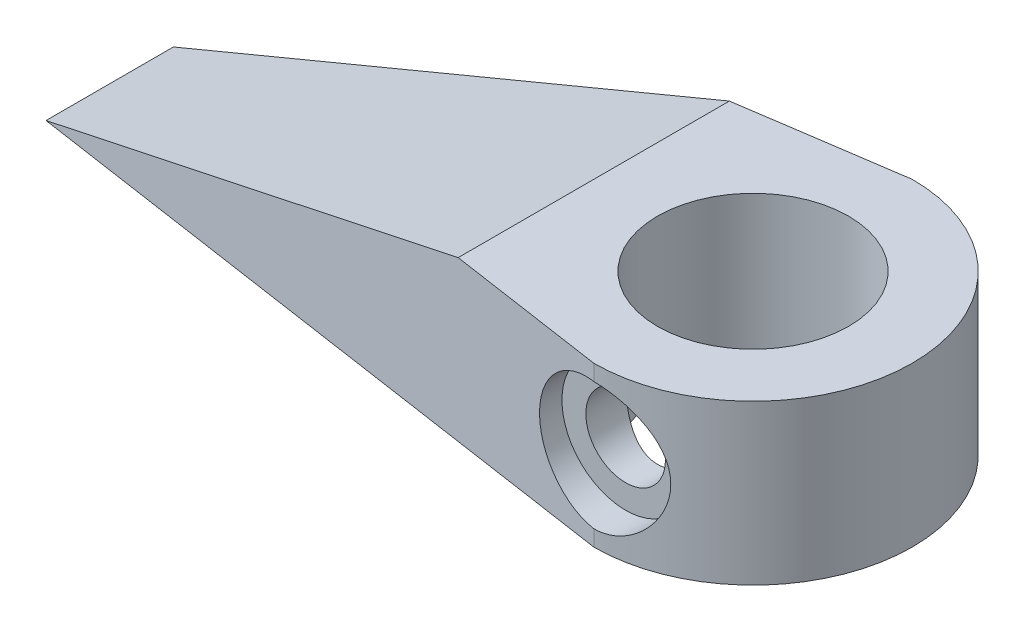
SolidWorks part; units mm, degrees
ref_plane "Front Plane" through (0, 0, 0) normal (0, 0, 1) x (1, 0, 0)
ref_plane "Top Plane" through (0, 0, 0) normal (0, 1, 0) x (1, 0, 0)
ref_plane "Right Plane" through (0, 0, 0) normal (1, 0, 0) x (0, 0, -1)
sketch "Sketch1" plane through (0, 0, 0) normal (0, 0, 1) x (1, 0, 0)
  line L0 (0, 0) -> (15.1987, 5)
  line L1 (15.1987, 5) -> (15.1987, 0)
  line L2 (15.1987, 0) -> (0, 0)
  dimension "D1" = 5
  dimension "D2" = 16
extrude "Boss-Extrude4" add sketch "Sketch1" along normal blind 4
sketch "Sketch7" plane through (0, 0, 0) normal (0, 1, 0) x (1, 0, 0)
  line L0 (15.1987, -2) -> (25.1987, -2) construction
  line L1 (15.1987, -4) -> (15.1987, 0) construction
  line L10 (20.1987, 3) -> (0, 0)
  line L11 (0, 0) -> (15.1987, 0)
  line L12 (15.1987, 0) -> (15.1987, -4)
  line L13 (15.1987, -4) -> (0, -4)
  line L14 (0, -4) -> (20.1987, -7)
  arc A0 (20.1987, -7) -> (20.1987, 3) centre (20.1987, -2) ccw
  dimension "D1" = 10
  dimension "D2" = 5
extrude "Boss-Extrude6" add sketch "Sketch7" along normal blind 5
sketch "Sketch10" plane through (0, 0, 0) normal (0, 0, 1) x (1, 0, 0)
  line L3 (0, 0) -> (0, 5)
  line L4 (0, 5) -> (15.1987, 5)
  line L5 (15.1987, 5) -> (0, 0)
extrude "Cut-Extrude3" cut sketch "Sketch10" against normal up to next
ref_plane "Plane1" through (0, 0, 2) normal (0, 0, 1) x (1, 0, 0)
sketch "Sketch9" plane through (0, 5, 0) normal (0, 1, 0) x (1, 0, 0)
  line L0 (-2.75, -2) -> (2.75, -2) construction
  circle A0 centre (20.1987, -2) radius 3
  arc A1 (20.1987, -7) -> (20.1987, 3) centre (20.1987, -2) ccw construction
  dimension "D1" = 6
extrude "Cut-Extrude2" cut sketch "Sketch9" against normal up to next
mirror "Mirror1" about plane through (0, 0, 2) normal (0, 0, 1) of "Cut-Extrude3"
ref_plane "Plane2" through (20.1987, 5, 7) normal (0, -1, 0) x (-1, 0, 0)
ref_plane "Plane3" through (0, 0, 7) normal (0, 0, 1) x (1, 0, 0)
sketch "Sketch12" plane through (0, 0, 7) normal (0, 0, 1) x (1, 0, 0)
  line L0 (20.1987, 5) -> (20.1987, 0) construction
  circle A0 centre (20.1987, 2.5) radius 1.25
  dimension "D1" = 2.5
extrude "Cut-Extrude4" cut sketch "Sketch12" against normal up to next
sketch "Sketch13" plane through (0, 0, 7) normal (0, 0, 1) x (1, 0, 0)
  circle A0 centre (20.1987, 2.5) radius 2
  dimension "D1" = 4
extrude "Cut-Extrude5" cut sketch "Sketch13" against normal blind 1
